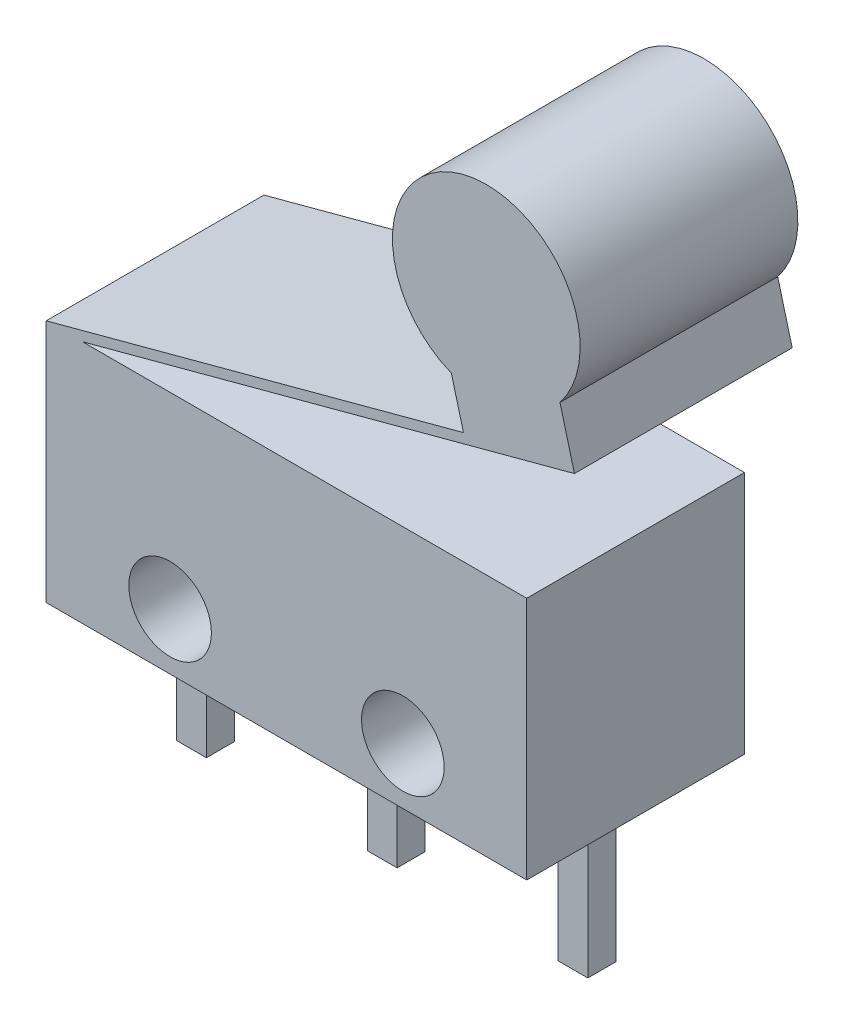
SolidWorks part; units mm, degrees
ref_plane "Front Plane" through (0, 0, 0) normal (0, 0, 1) x (1, 0, 0)
ref_plane "Top Plane" through (0, 0, 0) normal (0, 1, 0) x (1, 0, 0)
ref_plane "Right Plane" through (0, 0, 0) normal (1, 0, 0) x (0, 0, -1)
sketch "Sketch1" plane through (0, 0, 0) normal (0, 0, 1) x (1, 0, 0)
  line L0 (0, 6.5) -> (11.1152, 9.4783)
  line L1 (0, 0) -> (12.8, 0)
  line L2 (0, 0) -> (0, 6.5)
  line L3 (0.9659, 6.5) -> (12.8, 6.5)
  line L4 (12.8, 0) -> (12.8, 6.5)
  line L5 (14.0059, 10.2529) -> (14.0706, 10.0114)
  line L6 (14.0706, 10.0114) -> (0.9659, 6.5)
  line L7 (14.0706, 10.0114) -> (13.6849, 11.4593)
  line L9 (10.7911, 10.6878) -> (11.1152, 9.4783)
  arc A0 (13.6849, 11.4593) -> (10.7911, 10.6878) centre (11.7223, 13.0079) ccw
  circle A1 centre (3.3, 1.5) radius 1.1
  circle A2 centre (9.5, 1.5) radius 1.1
  point P16 (2.5875, 1.5179)
  point P17 (9.9827, 1.5179)
  point P18 (0, 0)
  dimension "D9" = 5
  dimension "D7" = 2.2
  dimension "D1" = 12.8
  dimension "D2" = 6.5
  dimension "D3" = 15
  dimension "D4" = 14.5
  dimension "D5" = 6.5
  dimension "D6" = 0.25
  dimension "D8" = 3.3
  dimension "D10" = 3.3
  dimension "D11" = 1.5
  dimension "D12" = 1.5
extrude "Boss-Extrude1" add sketch "Sketch1" along normal blind 5.8
sketch "Sketch2" plane through (0, 0, 0) normal (0, -1, 0) x (1, 0, 0)
  line L0 (6.0019, 3.2469) -> (6.7936, 3.2469)
  line L1 (0.9219, 3.2469) -> (1.7136, 3.2469)
  line L2 (0.9219, 3.2469) -> (0.9219, 2.4985)
  line L3 (0.9219, 2.4985) -> (1.7136, 2.4985)
  line L4 (1.7136, 3.2469) -> (1.7136, 2.4985)
  line L5 (6.0019, 3.2469) -> (6.0019, 2.4985)
  line L6 (6.0019, 2.4985) -> (6.7936, 2.4985)
  line L7 (6.7936, 3.2469) -> (6.7936, 2.4985)
  line L8 (11.0819, 3.2469) -> (11.8736, 3.2469)
  line L9 (11.0819, 3.2469) -> (11.0819, 2.4985)
  line L10 (11.0819, 2.4985) -> (11.8736, 2.4985)
  line L11 (11.8736, 3.2469) -> (11.8736, 2.4985)
  dimension "D1" = 3
extrude "Boss-Extrude2" add sketch "Sketch2" along normal blind 4
